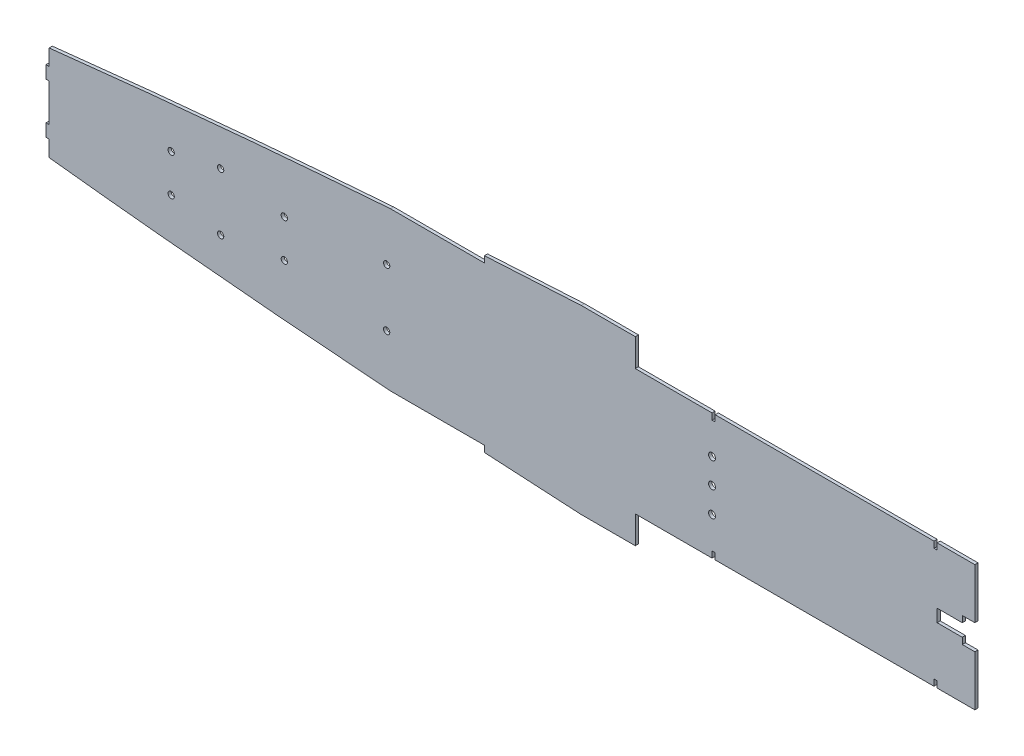
SolidWorks part; units mm, degrees
material "E-Glass Fiber"
ref_plane "Front Plane" through (0, 0, 0) normal (0, 0, 1) x (1, 0, 0)
ref_plane "Top Plane" through (0, 0, 0) normal (0, 1, 0) x (1, 0, 0)
ref_plane "Right Plane" through (0, 0, 0) normal (1, 0, 0) x (0, 0, -1)
sketch "Sketch1" plane through (0, 0, 0) normal (0, 0, 1) x (1, 0, 0)
  line L0 (0, 0) -> (508, 0) construction
  line L1 (508, 34.29) -> (508, 45.72)
  line L2 (508, 34.29) -> (635, 34.29)
  line L3 (508, 34.29) -> (508, -34.29)
  line L4 (508, -34.29) -> (635, -34.29)
  line L5 (635, 34.29) -> (635, -34.29)
  line L6 (508, 45.72) -> (383.5429, 45.72)
  line L7 (508, -45.72) -> (383.5429, -45.72)
  line L8 (508, -34.29) -> (508, -45.72)
  line L9 (161.29, 26.5379) -> (161.29, -26.5379)
  line L11 (161.29, 15.875) -> (159.7025, 15.875)
  line L12 (161.29, 15.875) -> (161.29, 9.525)
  line L13 (161.29, 9.525) -> (159.7025, 9.525)
  line L14 (159.7025, 15.875) -> (159.7025, 9.525)
  line L15 (161.29, -9.525) -> (159.7025, -9.525)
  line L16 (161.29, -9.525) -> (161.29, -15.875)
  line L17 (161.29, -15.875) -> (159.7025, -15.875)
  line L18 (159.7025, -9.525) -> (159.7025, -15.875)
  spline S0 degree 4 poles (0, 0) (0.0018, 0.005) (0.0062, 0.0145) (0.0182, 0.0319) (0.0463, 0.0632) (0.089, 0.1023) (0.1469, 0.1479) (0.229, 0.206) (0.3278, 0.2692) (0.4437, 0.3374) (0.5768, 0.4102) (0.7706, 0.5103) (1.0712, 0.6544) (1.5816, 0.8779) (2.4946, 1.2372) (4.1395, 1.8115) (7.1625, 2.7351) (12.8366, 4.2347) (22.7381, 6.4789) (39.5608, 9.7589) (62.6587, 13.6285) (90.6557, 17.7631) (121.7908, 21.8822) (152.9704, 25.646) (184.1842, 29.1144) (215.4253, 32.3259) (246.6896, 35.3031) (277.974, 38.06) (309.2766, 40.6034) (340.5957, 42.9338) (371.9303, 45.0455) (403.2798, 46.9255) (430.7232, 48.3462) (454.255, 49.3766) (473.2313, 50.0594) (486.006, 50.4329) (496.5006, 50.6673) (503.0715, 50.7648) (506.3571, 50.7959) (508, 50.8) knots 0 0 0 0 0 0.000041 0.000082 0.000164 0.000329 0.000493 0.000658 0.000951 0.001245 0.001545 0.001844 0.002657 0.003853 0.005902 0.009516 0.016281 0.028569 0.051794 0.088907 0.150314 0.211721 0.273128 0.334535 0.395942 0.457348 0.518755 0.580162 0.641569 0.702976 0.764383 0.825789 0.887196 0.9179 0.948603 0.974302 0.987151 1 1 1 1 1 construction
  spline S1 degree 4 poles (0, 0) (0.0018, 0.005) (0.0062, 0.0145) (0.0182, 0.0319) (0.0463, 0.0632) (0.089, 0.1023) (0.1469, 0.1479) (0.229, 0.206) (0.3278, 0.2692) (0.4437, 0.3374) (0.5768, 0.4102) (0.7706, 0.5103) (1.0712, 0.6544) (1.5816, 0.8779) (2.4946, 1.2372) (4.1395, 1.8115) (7.1625, 2.7351) (12.8366, 4.2347) (22.7381, 6.4789) (39.5608, 9.7589) (62.6587, 13.6285) (90.6557, 17.7631) (121.7908, 21.8822) (152.9704, 25.646) (184.1842, 29.1144) (215.4253, 32.3259) (246.6896, 35.3031) (277.974, 38.06) (309.2766, 40.6034) (340.5957, 42.9338) (371.9303, 45.0455) (403.2798, 46.9255) (430.7232, 48.3462) (454.255, 49.3766) (473.2313, 50.0594) (486.006, 50.4329) (496.5006, 50.6673) (503.0715, 50.7648) (506.3571, 50.7959) (508, 50.8) knots 0 0 0 0 0 0.000041 0.000082 0.000164 0.000329 0.000493 0.000658 0.000951 0.001245 0.001545 0.001844 0.002657 0.003853 0.005902 0.009516 0.016281 0.028569 0.051794 0.088907 0.150314 0.211721 0.273128 0.334535 0.395942 0.457348 0.518755 0.580162 0.641569 0.702976 0.764383 0.825789 0.887196 0.9179 0.948603 0.974302 0.987151 1 1 1 1 1 construction
  spline S4 degree 4 poles (0, 0) (0.0018, -0.005) (0.0062, -0.0145) (0.0182, -0.0319) (0.0463, -0.0632) (0.089, -0.1023) (0.1469, -0.1479) (0.229, -0.206) (0.3278, -0.2692) (0.4437, -0.3374) (0.5768, -0.4102) (0.7706, -0.5103) (1.0712, -0.6544) (1.5816, -0.8779) (2.4946, -1.2372) (4.1395, -1.8115) (7.1625, -2.7351) (12.8366, -4.2347) (22.7381, -6.4789) (39.5608, -9.7589) (62.6587, -13.6285) (90.6557, -17.7631) (121.7908, -21.8822) (152.9704, -25.646) (184.1842, -29.1144) (215.4253, -32.3259) (246.6896, -35.3031) (277.974, -38.06) (309.2766, -40.6034) (340.5957, -42.9338) (371.9303, -45.0455) (403.2798, -46.9255) (430.7232, -48.3462) (454.255, -49.3766) (473.2313, -50.0594) (486.006, -50.4329) (496.5006, -50.6673) (503.0715, -50.7648) (506.3571, -50.7959) (508, -50.8) knots 0 0 0 0 0 0.000041 0.000082 0.000164 0.000329 0.000493 0.000658 0.000951 0.001245 0.001545 0.001844 0.002657 0.003853 0.005902 0.009516 0.016281 0.028569 0.051794 0.088907 0.150314 0.211721 0.273128 0.334535 0.395942 0.457348 0.518755 0.580162 0.641569 0.702976 0.764383 0.825789 0.887196 0.9179 0.948603 0.974302 0.987151 1 1 1 1 1 construction
  spline S7 degree 1 poles (6.9536, 0) (508.0063, -48.26) knots 0 0 1 1 construction
  spline S8 degree 1 poles (6.9536, 0) (508.0063, 48.26) knots 0 0 1 1 construction
  spline S9 degree 3 poles (508.0063, -48.26) (505.389, -48.2535) (500.1595, -48.1854) (489.6619, -47.9832) (471.2967, -47.4768) (445.0522, -46.4694) (413.5702, -44.9339) (371.608, -42.5248) (319.1882, -38.9156) (256.3481, -33.728) (204.0482, -28.6792) (162.2644, -24.1404) (130.9623, -20.4508) (99.7076, -16.4227) (73.7194, -12.7048) (52.9887, -9.4159) (37.4884, -6.7357) (24.6309, -4.2526) (15.7185, -2.2776) (10.6685, -1.0328) (8.1898, -0.3612) (6.9536, 0) knots 0.013175 0.013175 0.013175 0.013175 0.028594 0.044013 0.074852 0.136528 0.198205 0.259881 0.383235 0.506588 0.629941 0.691617 0.753294 0.81497 0.876647 0.907485 0.938323 0.969162 0.984581 0.99229 1 1 1 1
  spline S10 degree 3 poles (6.9536, 0) (8.1898, 0.3612) (10.6685, 1.0328) (15.7185, 2.2776) (24.6309, 4.2526) (37.4884, 6.7357) (52.9887, 9.4159) (73.7194, 12.7048) (99.7076, 16.4227) (130.9623, 20.4508) (162.2644, 24.1404) (204.0482, 28.6792) (256.3481, 33.728) (319.1882, 38.9156) (371.608, 42.5248) (413.5702, 44.9339) (445.0522, 46.4694) (471.2967, 47.4768) (489.6619, 47.9832) (500.1595, 48.1854) (505.389, 48.2535) (508.0063, 48.26) knots 0.013175 0.013175 0.013175 0.013175 0.020885 0.028594 0.044013 0.074852 0.10569 0.136528 0.198205 0.259881 0.321558 0.383235 0.506588 0.629941 0.753294 0.81497 0.876647 0.938323 0.969162 0.984581 1 1 1 1
  dimension "D1" = 508
  dimension "D2" = 68.58
  dimension "D3" = 45.72
  dimension "D4" = 127
  dimension "D5" = 161.29
  dimension "D7" = 1.5875
  dimension "D8" = 6.35
  dimension "D9" = 19.05
  dimension "D6" = 2.54
extrude "Boss-Extrude1" add sketch "Sketch1" along normal blind 1.5875
sketch "Sketch10" plane through (0, 0, 0) normal (0, 0, -1) x (-1, 0, 0)
  line L0 (-635, 34.29) -> (-635, -34.29) construction
  line L1 (-628.65, 34.29) -> (-635, 34.29)
  line L2 (-628.65, 34.29) -> (-628.65, -34.29)
  line L3 (-628.65, -34.29) -> (-635, -34.29)
  line L4 (-635, 34.29) -> (-635, -34.29)
  line L5 (-508, 34.29) -> (-635, 34.29) construction
  line L6 (-508, -34.29) -> (-635, -34.29) construction
  dimension "D1" = 6.35
extrude "Cut-Extrude5" cut sketch "Sketch10" against normal through all
sketch "Sketch2" plane through (628.65, 0, 0) normal (1, 0, 0) x (0, 0, -1)
  line L0 (-0.7938, 34.29) -> (-0.7937, -34.29) construction
  line L1 (0, -34.29) -> (0, 34.29) construction
  line L2 (-1.5875, -34.29) -> (-1.5875, 34.29) construction
  line L4 (-1.5875, -34.29) -> (0, -34.29) construction
  line L5 (-1.5875, 34.29) -> (0, 34.29) construction
  line L7 (0, 0) -> (-1.5875, 0) construction
sketch "Sketch3" plane through (0, 0, 1.5875) normal (0, 0, 1) x (1, 0, 0)
  line L0 (508, 45.72) -> (429.9476, 45.72) construction
  line L1 (508, 34.29) -> (457.2, 34.29)
  line L2 (508, 34.29) -> (508, 45.72)
  line L3 (508, 45.72) -> (457.2, 45.72)
  line L4 (457.2, 34.29) -> (457.2, 45.72)
  line L5 (508, -45.72) -> (429.9476, -45.72) construction
  line L6 (508, -34.29) -> (457.2, -34.29)
  line L7 (508, -34.29) -> (508, -45.72)
  line L8 (508, -45.72) -> (457.2, -45.72)
  line L9 (457.2, -34.29) -> (457.2, -45.72)
  line L10 (628.65, 34.29) -> (628.65, -34.29) construction
  line L11 (622.3, 3.175) -> (609.6, 3.175)
  line L12 (161.29, 9.525) -> (161.29, -9.525) construction
  line L13 (622.3, -3.175) -> (609.6, -3.175)
  line L14 (609.6, 3.175) -> (609.6, -3.175)
  line L15 (161.29, 0) -> (628.65, 0) construction
  line L16 (628.65, -34.29) -> (628.65, 34.29) construction
  line L17 (622.3, -3.175) -> (622.3, -6.35)
  line L18 (622.3, 6.35) -> (628.65, 6.35)
  line L19 (622.3, 6.35) -> (622.3, 3.175)
  line L20 (622.3, -6.35) -> (628.65, -6.35)
  line L21 (628.65, 6.35) -> (628.65, -6.35)
  line L22 (635, 34.29) -> (457.2, 34.29)
  line L23 (635, 34.29) -> (635, 31.75)
  line L24 (635, 31.75) -> (457.2, 31.75)
  line L25 (457.2, 34.29) -> (457.2, 31.75)
  line L26 (635, -34.29) -> (457.2, -34.29)
  line L27 (635, -34.29) -> (635, -31.75)
  line L28 (635, -31.75) -> (457.2, -31.75)
  line L29 (457.2, -34.29) -> (457.2, -31.75)
  line L30 (508, -34.29) -> (628.65, -34.29) construction
  line L31 (508, 34.29) -> (628.65, 34.29) construction
  dimension "D1" = 50.8
  dimension "D2" = 6.35
  dimension "D3" = 19.05
  dimension "D4" = 12.7
  dimension "D5" = 6.35
  dimension "D6" = 2.54
  dimension "D7" = 6.35
  dimension "D8" = 6.35
extrude "Cut-Extrude1" cut sketch "Sketch3" against normal through all
sketch "Sketch4" plane through (0, 0, 1.5875) normal (0, 0, 1) x (1, 0, 0)
  line L0 (628.65, -31.75) -> (457.2, -31.75) construction
  line L1 (609.6, 3.175) -> (609.6, -3.175) construction
  line L2 (497.5542, 28.575) -> (495.9667, 28.575)
  line L3 (495.9667, 31.75) -> (495.9667, 28.575)
  line L4 (497.5542, 31.75) -> (497.5542, 28.575)
  line L5 (628.65, 31.75) -> (457.2, 31.75) construction
  line L6 (609.6, 31.75) -> (608.0125, 31.75)
  line L7 (609.6, 31.75) -> (609.6, 28.575)
  line L8 (609.6, 28.575) -> (608.0125, 28.575)
  line L9 (608.0125, 31.75) -> (608.0125, 28.575)
  line L11 (497.5542, 31.75) -> (495.9667, 31.75)
  line L12 (497.5542, -31.75) -> (495.9667, -31.75)
  line L13 (495.9667, -28.575) -> (495.9667, -31.75)
  line L14 (497.5542, -28.575) -> (497.5542, -31.75)
  line L15 (497.5542, -28.575) -> (495.9667, -28.575)
  line L16 (609.6, -31.75) -> (608.0125, -31.75)
  line L17 (608.0125, -28.575) -> (608.0125, -31.75)
  line L18 (609.6, -28.575) -> (609.6, -31.75)
  line L19 (609.6, -28.575) -> (608.0125, -28.575)
  dimension "D1" = 3.175
  dimension "D2" = 1.5875
  dimension "D5" = 112.0457
  dimension "D3" = 2
  dimension "D4" = 2
extrude "Cut-Extrude2" cut sketch "Sketch4" against normal through all
sketch "Sketch6" plane through (0, 0, 1.5875) normal (0, 0, 1) x (1, 0, 0)
  line L0 (381, 43.0197) -> (381, -43.0197) construction
  line L1 (628.65, 6.35) -> (628.65, 31.75) construction
  line L2 (333.6619, 39.8447) -> (381, 39.8447)
  line L3 (381, 39.8447) -> (381, 43.0197)
  line L4 (161.29, 0) -> (609.6, 0) construction
  line L6 (609.6, 3.175) -> (609.6, -3.175) construction
  line L7 (381, 43.0197) -> (333.6619, 43.0197)
  line L8 (333.6619, 43.0197) -> (333.6619, 39.8447)
  line L9 (333.6619, -43.0197) -> (333.6619, -39.8447)
  line L10 (381, -43.0197) -> (333.6619, -43.0197)
  line L11 (381, -39.8447) -> (381, -43.0197)
  line L12 (333.6619, -39.8447) -> (381, -39.8447)
  line L13 (161.29, 9.525) -> (161.29, -9.525) construction
  spline S0 degree 3 poles (161.29, 23.9816) (161.6168, 24.0187) (172.3834, 25.2396) (204.0482, 28.6792) (256.3481, 33.728) (319.1882, 38.9156) (371.608, 42.5248) (408.5368, 44.6449) (424.4886, 45.456) (429.9476, 45.72) knots 0.319627 0.319627 0.319627 0.319627 0.321558 0.383235 0.506588 0.629941 0.753294 0.81497 0.847055 0.847055 0.847055 0.847055 construction
  spline S2 degree 3 poles (429.9476, -45.72) (424.4886, -45.456) (408.5368, -44.6449) (371.608, -42.5248) (319.1882, -38.9156) (256.3481, -33.728) (204.0482, -28.6792) (172.3834, -25.2396) (161.6168, -24.0187) (161.29, -23.9816) knots 0.166121 0.166121 0.166121 0.166121 0.198205 0.259881 0.383235 0.506588 0.629941 0.691617 0.693548 0.693548 0.693548 0.693548 construction
  spline S3 degree 3 poles (161.29, 23.9816) (161.6168, 24.0187) (172.3834, 25.2396) (204.0482, 28.6792) (256.3481, 33.728) (319.1882, 38.9156) (371.608, 42.5248) (408.5368, 44.6449) (424.4886, 45.456) (429.9476, 45.72) knots 0.319627 0.319627 0.319627 0.319627 0.321558 0.383235 0.506588 0.629941 0.753294 0.81497 0.847055 0.847055 0.847055 0.847055 construction
  dimension "D1" = 247.65
  dimension "D2" = 3.175
extrude "Cut-Extrude3" cut sketch "Sketch6" against normal through all
sketch "Sketch7" plane through (0, 0, 1.5875) normal (0, 0, 1) x (1, 0, 0)
  line L1 (609.6, 0) -> (575.4012, 0) construction
  line L2 (609.6, 3.175) -> (609.6, -3.175) construction
  circle A0 centre (331.6888, 14.478) radius 1.5875
  circle A1 centre (331.6888, -14.478) radius 1.5875
  circle A2 centre (247.8688, 14.478) radius 1.5875
  circle A3 centre (247.8688, -14.478) radius 1.5875
  dimension "D1" = 3.175
  dimension "D3" = 83.82
  dimension "D2" = 28.956
extrude "ARTS4 mount" cut sketch "Sketch7" against normal through all
sketch "Sketch8" plane through (0, 0, 1.5875) normal (0, 0, 1) x (1, 0, 0)
  line L0 (609.6, 0) -> (598.1663, 0) construction
  line L1 (609.6, 3.175) -> (609.6, -3.175) construction
  circle A0 centre (280.0184, 9.525) radius 1.5875
  circle A1 centre (280.0184, -9.525) radius 1.5875
  circle A2 centre (222.8938, -9.525) radius 1.5875
  circle A3 centre (222.8938, 9.525) radius 1.5875
  dimension "D3" = 3.175
  dimension "D1" = 19.05
  dimension "D2" = 57.1246
extrude "Telemetrum Mount" cut sketch "Sketch8" against normal through all
sketch "Sketch9" plane through (0, 0, 1.5875) normal (0, 0, 1) x (1, 0, 0)
  line L0 (609.6, 0) -> (407.9934, 0) construction
  line L1 (609.6, 3.175) -> (609.6, -3.175) construction
  circle A0 centre (495.9667, -12.7) radius 1.7462
  circle A1 centre (495.9667, 12.7) radius 1.7462
  circle A2 centre (495.9667, 0) radius 1.7462
  dimension "D1" = 3.4925
  dimension "D2" = 12.7
extrude "Cut-Extrude4" cut sketch "Sketch9" against normal through all
